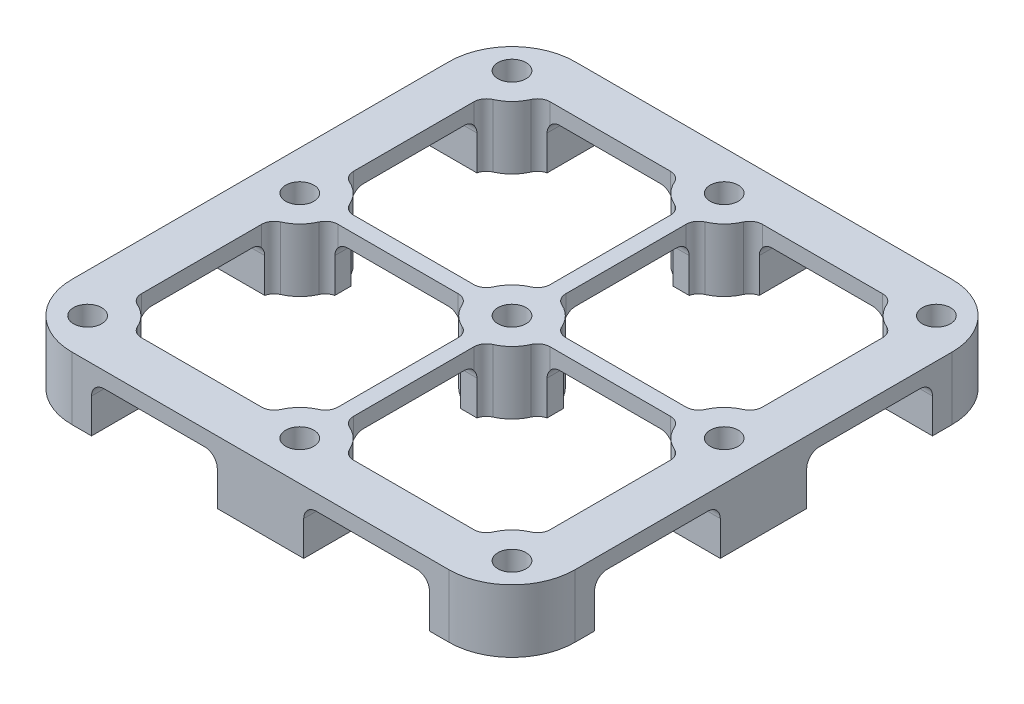
SolidWorks part; units mm, degrees
ref_plane "Front Plane" through (0, 0, 0) normal (0, 0, 1) x (1, 0, 0)
ref_plane "Top Plane" through (0, 0, 0) normal (0, 1, 0) x (1, 0, 0)
ref_plane "Right Plane" through (0, 0, 0) normal (1, 0, 0) x (0, 0, -1)
sketch "Sketch1" plane through (0, 0, 0) normal (0, 1, 0) x (1, 0, 0)
  line L0 (0, 50.8) -> (101.6, 50.8) construction
  line L1 (12.7, 0) -> (88.9, 0)
  line L2 (0, 12.7) -> (0, 88.9)
  line L3 (12.7, 101.6) -> (88.9, 101.6)
  line L4 (101.6, 12.7) -> (101.6, 88.9)
  line L5 (50.8, 101.6) -> (50.8, 0) construction
  line L6 (7.9375, 93.6625) -> (7.9375, 7.9375) construction
  line L7 (7.9375, 7.9375) -> (93.6625, 7.9375) construction
  line L8 (93.6625, 7.9375) -> (93.6625, 93.6625) construction
  line L9 (93.6625, 93.6625) -> (7.9375, 93.6625) construction
  line L10 (17.2213, 52.3875) -> (41.5162, 52.3875)
  line L11 (92.075, 84.3787) -> (92.075, 60.0838)
  line L12 (84.3787, 52.3875) -> (60.0838, 52.3875)
  line L13 (17.2213, 92.075) -> (41.5162, 92.075)
  line L14 (49.2125, 84.3787) -> (49.2125, 60.0838)
  line L15 (9.525, 84.3787) -> (9.525, 60.0838)
  line L16 (52.3875, 84.3787) -> (52.3875, 60.0838)
  line L17 (84.3787, 92.075) -> (60.0838, 92.075)
  line L18 (52.3875, 17.2213) -> (52.3875, 41.5162)
  line L19 (84.3787, 49.2125) -> (60.0838, 49.2125)
  line L20 (92.075, 17.2213) -> (92.075, 41.5162)
  line L21 (84.3787, 9.525) -> (60.0838, 9.525)
  line L22 (9.525, 17.2213) -> (9.525, 41.5162)
  line L23 (17.2213, 49.2125) -> (41.5162, 49.2125)
  line L24 (49.2125, 17.2213) -> (49.2125, 41.5162)
  line L25 (17.2213, 9.525) -> (41.5162, 9.525)
  arc A0 (12.7, 0) -> (0, 12.7) centre (12.7, 12.7) cw
  arc A1 (88.9, 0) -> (101.6, 12.7) centre (88.9, 12.7) ccw
  arc A2 (88.9, 101.6) -> (101.6, 88.9) centre (88.9, 88.9) cw
  arc A3 (0, 88.9) -> (12.7, 101.6) centre (12.7, 88.9) cw
  circle A4 centre (7.9375, 93.6625) radius 2.8391
  circle A5 centre (50.8, 93.6625) radius 2.8391
  circle A6 centre (93.6625, 93.6625) radius 2.8391
  circle A7 centre (50.8, 50.8) radius 2.8391
  circle A8 centre (93.6625, 50.8) radius 2.8391
  circle A9 centre (50.8, 7.9375) radius 2.8391
  circle A10 centre (93.6625, 7.9375) radius 2.8391
  circle A11 centre (7.9375, 50.8) radius 2.8391
  circle A12 centre (7.9375, 7.9375) radius 2.8391
  arc A13 (11.0331, 86.6996) -> (14.9004, 90.5669) centre (7.9375, 93.6625) ccw
  arc A14 (43.8371, 90.5669) -> (47.7044, 86.6996) centre (50.8, 93.6625) ccw
  arc A15 (47.7044, 57.7629) -> (43.8371, 53.8956) centre (50.8, 50.8) ccw
  arc A16 (11.0331, 57.7629) -> (14.9004, 53.8956) centre (7.9375, 50.8) cw
  arc A17 (47.7044, 86.6996) -> (49.2125, 84.3787) centre (46.6725, 84.3787) cw
  arc A18 (43.8371, 90.5669) -> (41.5162, 92.075) centre (41.5162, 89.535) ccw
  arc A19 (14.9004, 90.5669) -> (17.2213, 92.075) centre (17.2213, 89.535) cw
  arc A20 (11.0331, 86.6996) -> (9.525, 84.3787) centre (12.065, 84.3787) ccw
  arc A21 (11.0331, 57.7629) -> (9.525, 60.0838) centre (12.065, 60.0838) cw
  arc A22 (14.9004, 53.8956) -> (17.2213, 52.3875) centre (17.2213, 54.9275) ccw
  arc A23 (43.8371, 53.8956) -> (41.5162, 52.3875) centre (41.5162, 54.9275) cw
  arc A24 (47.7044, 57.7629) -> (49.2125, 60.0838) centre (46.6725, 60.0838) ccw
  arc A25 (86.6996, 90.5669) -> (84.3787, 92.075) centre (84.3787, 89.535) ccw
  arc A26 (90.5669, 86.6996) -> (86.6996, 90.5669) centre (93.6625, 93.6625) cw
  arc A27 (90.5669, 86.6996) -> (92.075, 84.3787) centre (89.535, 84.3787) cw
  arc A28 (90.5669, 57.7629) -> (92.075, 60.0838) centre (89.535, 60.0838) ccw
  arc A29 (90.5669, 57.7629) -> (86.6996, 53.8956) centre (93.6625, 50.8) ccw
  arc A30 (86.6996, 53.8956) -> (84.3787, 52.3875) centre (84.3787, 54.9275) cw
  arc A31 (57.7629, 53.8956) -> (60.0838, 52.3875) centre (60.0838, 54.9275) ccw
  arc A32 (53.8956, 57.7629) -> (57.7629, 53.8956) centre (50.8, 50.8) cw
  arc A33 (53.8956, 57.7629) -> (52.3875, 60.0838) centre (54.9275, 60.0838) cw
  arc A34 (53.8956, 86.6996) -> (52.3875, 84.3787) centre (54.9275, 84.3787) ccw
  arc A35 (57.7629, 90.5669) -> (53.8956, 86.6996) centre (50.8, 93.6625) cw
  arc A36 (57.7629, 90.5669) -> (60.0838, 92.075) centre (60.0838, 89.535) cw
  arc A37 (53.8956, 43.8371) -> (52.3875, 41.5162) centre (54.9275, 41.5162) ccw
  arc A38 (53.8956, 43.8371) -> (57.7629, 47.7044) centre (50.8, 50.8) ccw
  arc A39 (57.7629, 47.7044) -> (60.0838, 49.2125) centre (60.0838, 46.6725) cw
  arc A40 (86.6996, 47.7044) -> (84.3787, 49.2125) centre (84.3787, 46.6725) ccw
  arc A41 (90.5669, 43.8371) -> (86.6996, 47.7044) centre (93.6625, 50.8) cw
  arc A42 (90.5669, 43.8371) -> (92.075, 41.5162) centre (89.535, 41.5162) cw
  arc A43 (90.5669, 14.9004) -> (92.075, 17.2213) centre (89.535, 17.2213) ccw
  arc A44 (90.5669, 14.9004) -> (86.6996, 11.0331) centre (93.6625, 7.9375) ccw
  arc A45 (86.6996, 11.0331) -> (84.3787, 9.525) centre (84.3787, 12.065) cw
  arc A46 (43.8371, 11.0331) -> (41.5162, 9.525) centre (41.5162, 12.065) cw
  arc A47 (57.7629, 11.0331) -> (60.0838, 9.525) centre (60.0838, 12.065) ccw
  arc A48 (57.7629, 11.0331) -> (53.8956, 14.9004) centre (50.8, 7.9375) ccw
  arc A49 (53.8956, 14.9004) -> (52.3875, 17.2213) centre (54.9275, 17.2213) cw
  arc A50 (11.0331, 14.9004) -> (9.525, 17.2213) centre (12.065, 17.2213) cw
  arc A51 (11.0331, 43.8371) -> (9.525, 41.5162) centre (12.065, 41.5162) ccw
  arc A52 (11.0331, 43.8371) -> (14.9004, 47.7044) centre (7.9375, 50.8) ccw
  arc A53 (14.9004, 47.7044) -> (17.2213, 49.2125) centre (17.2213, 46.6725) cw
  arc A54 (43.8371, 47.7044) -> (41.5162, 49.2125) centre (41.5162, 46.6725) ccw
  arc A55 (47.7044, 43.8371) -> (43.8371, 47.7044) centre (50.8, 50.8) cw
  arc A56 (47.7044, 43.8371) -> (49.2125, 41.5162) centre (46.6725, 41.5162) cw
  arc A57 (47.7044, 14.9004) -> (49.2125, 17.2213) centre (46.6725, 17.2213) ccw
  arc A58 (43.8371, 11.0331) -> (47.7044, 14.9004) centre (50.8, 7.9375) cw
  arc A59 (14.9004, 11.0331) -> (17.2213, 9.525) centre (17.2213, 12.065) ccw
  arc A60 (11.0331, 14.9004) -> (14.9004, 11.0331) centre (7.9375, 7.9375) cw
  point P7 (0, 0)
  point P10 (101.6, 0)
  point P15 (0, 101.6)
  point P22 (7.9375, 50.8)
  point P25 (50.8, 93.6625)
  dimension "D3" = 12.7
  dimension "D5" = 5.6781
  dimension "D8" = 7.62
  dimension "D13" = 2.54
  dimension "D1" = 101.6
  dimension "D2" = 101.6
  dimension "D4" = 85.725
  dimension "D6" = 3
  dimension "D7" = 3
extrude "Boss-Extrude1" add sketch "Sketch1" along normal blind 12.7
sketch "Sketch2" plane through (0, 0, 0) normal (0, 0, 1) x (1, 0, 0)
  line L0 (12.7, 0) -> (88.9, 0) construction
  line L1 (16.6687, 0) -> (42.0688, 0)
  line L2 (16.6687, 0) -> (16.6687, 6.985)
  line L3 (19.2088, 9.525) -> (39.5287, 9.525)
  line L4 (42.0688, 0) -> (42.0688, 6.985)
  line L5 (12.7, 12.7) -> (88.9, 12.7) construction
  line L6 (29.3687, 9.525) -> (29.3687, 0) construction
  line L9 (72.2313, 9.525) -> (72.2313, 0) construction
  line L10 (59.5312, 0) -> (84.9313, 0)
  line L11 (59.5312, 0) -> (59.5312, 6.985)
  line L12 (62.0713, 9.525) -> (82.3912, 9.525)
  line L13 (84.9313, 0) -> (84.9313, 6.985)
  line L14 (0, 12.7) -> (0, 0) construction
  arc A0 (82.3912, 9.525) -> (84.9313, 6.985) centre (82.3912, 6.985) cw
  arc A1 (59.5312, 6.985) -> (62.0713, 9.525) centre (62.0712, 6.985) cw
  arc A2 (39.5287, 9.525) -> (42.0688, 6.985) centre (39.5288, 6.985) cw
  arc A3 (16.6687, 6.985) -> (19.2088, 9.525) centre (19.2087, 6.985) cw
  point P24 (42.0688, 9.525)
  point P27 (16.6687, 9.525)
  dimension "D5" = 2.54
  dimension "D1" = 3.175
  dimension "D2" = 42.8625
  dimension "D3" = 25.4
  dimension "D4" = 29.3687
extrude "Cut-Extrude1" cut sketch "Sketch2" against normal through all
sketch "Sketch3" plane through (0, 0, 0) normal (-1, 0, 0) x (0, 0, 1)
  line L0 (-88.9, 0) -> (-12.7, 0) construction
  line L1 (-84.9313, 0) -> (-59.5312, 0)
  line L2 (-84.9313, 0) -> (-84.9313, 6.985)
  line L3 (-82.3912, 9.525) -> (-62.0713, 9.525)
  line L4 (-59.5312, 0) -> (-59.5312, 6.985)
  line L5 (-72.2313, 9.525) -> (-72.2313, 0) construction
  line L6 (-16.6687, 0) -> (-42.0688, 0)
  line L7 (-16.6687, 0) -> (-16.6687, 6.985)
  line L8 (-19.2088, 9.525) -> (-39.5287, 9.525)
  line L9 (-42.0688, 0) -> (-42.0688, 6.985)
  line L10 (-29.3687, 9.525) -> (-29.3687, 0) construction
  line L11 (-88.9, 12.7) -> (-12.7, 12.7) construction
  line L13 (-101.6, 12.7) -> (-101.6, 0) construction
  arc A0 (-16.6687, 6.985) -> (-19.2088, 9.525) centre (-19.2087, 6.985) ccw
  arc A1 (-39.5287, 9.525) -> (-42.0688, 6.985) centre (-39.5288, 6.985) ccw
  arc A2 (-62.0713, 9.525) -> (-59.5312, 6.985) centre (-62.0712, 6.985) cw
  arc A3 (-84.9313, 6.985) -> (-82.3912, 9.525) centre (-82.3912, 6.985) cw
  point P24 (-59.5312, 9.525)
  point P27 (-84.9313, 9.525)
  dimension "D5" = 2.54
  dimension "D1" = 42.8625
  dimension "D2" = 25.4
  dimension "D3" = 3.175
  dimension "D4" = 29.3687
extrude "Cut-Extrude2" cut sketch "Sketch3" against normal through all
